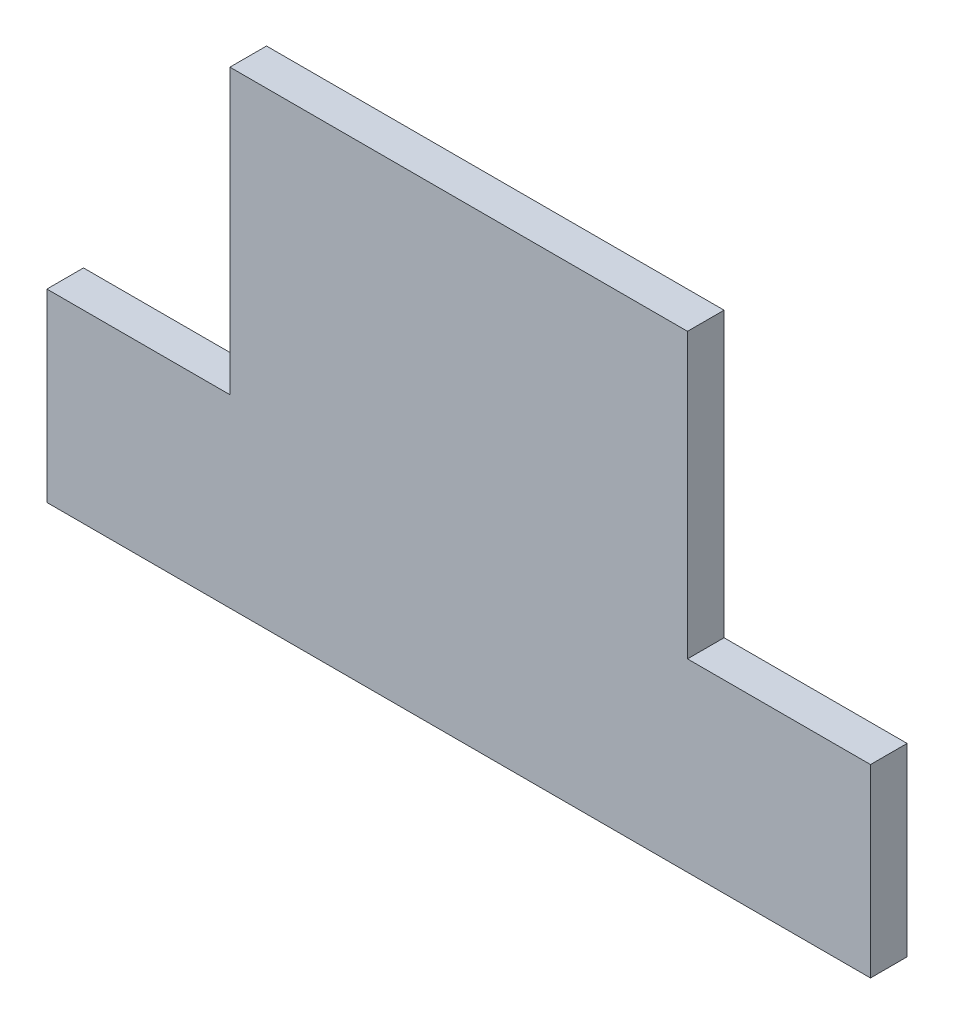
SolidWorks part; units mm, degrees
ref_plane "Front Plane" through (0, 0, 0) normal (0, 0, 1) x (1, 0, 0)
ref_plane "Top Plane" through (0, 0, 0) normal (0, 1, 0) x (1, 0, 0)
ref_plane "Right Plane" through (0, 0, 0) normal (1, 0, 0) x (0, 0, -1)
sketch "Sketch1" plane through (0, 0, 0) normal (0, 0, 1) x (1, 0, 0)
  line L1 (23.5149, -16.7) -> (-21.4851, -16.7)
  line L2 (23.5149, -16.7) -> (23.5149, -6.6)
  line L3 (23.5149, -6.6) -> (-21.4851, -6.6)
  line L4 (-21.4851, -16.7) -> (-21.4851, -6.6)
  line L5 (23.5149, -16.7) -> (-21.4851, -6.6) construction
  line L6 (23.5149, -6.6) -> (-21.4851, -16.7) construction
  line L7 (-11.4851, 8.9) -> (13.5149, 8.9)
  line L8 (-11.4851, 8.9) -> (-11.4851, -6.6)
  line L9 (-11.4851, -6.6) -> (13.5149, -6.6)
  line L10 (13.5149, 8.9) -> (13.5149, -6.6)
  line L11 (-11.4851, 8.9) -> (13.5149, -6.6) construction
  line L12 (-11.4851, -6.6) -> (13.5149, 8.9) construction
  point P4 (1.0149, -11.65)
  point P11 (1.0149, 1.15)
extrude "Boss-Extrude1" add sketch "Sketch1" along normal blind 2 contours L4 L1 L2 L3 | L10 L7 L8 L3
